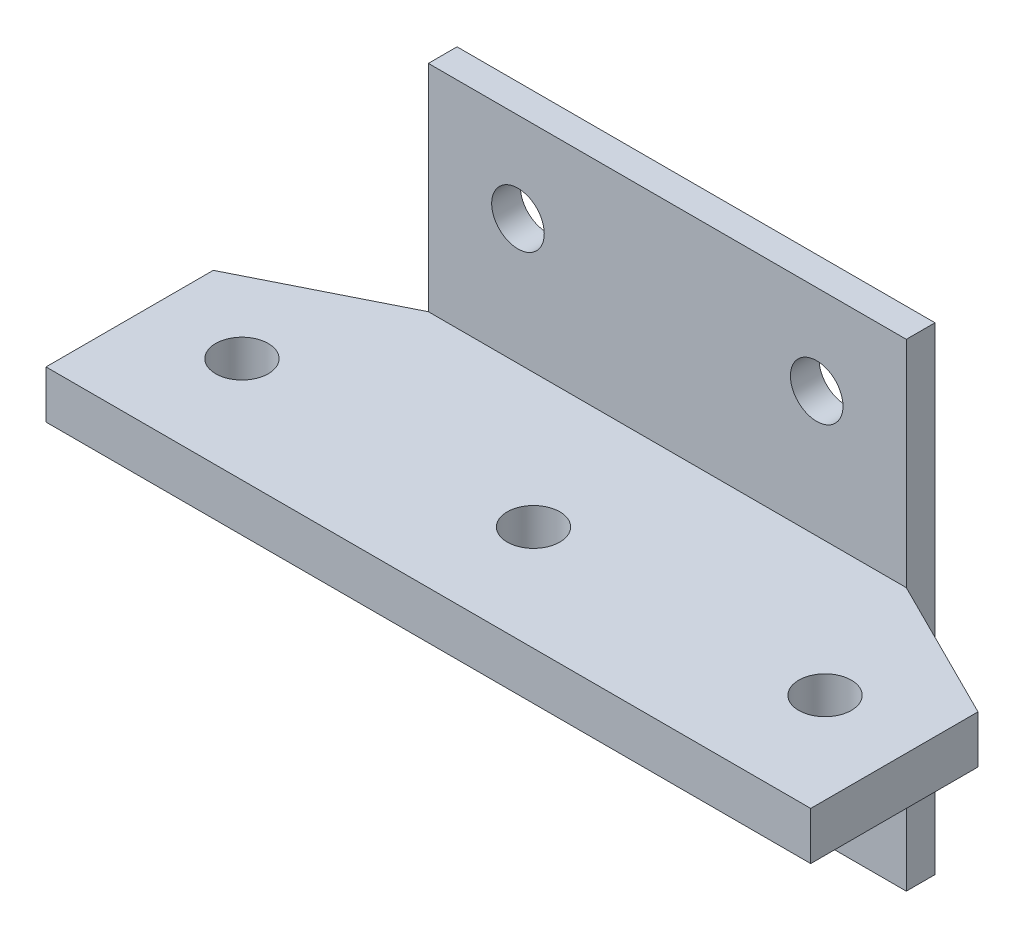
SolidWorks part; units mm, degrees
ref_plane "前视基准面" through (0, 0, 0) normal (0, 0, 1) x (1, 0, 0)
ref_plane "上视基准面" through (0, 0, 0) normal (0, 1, 0) x (1, 0, 0)
ref_plane "右视基准面" through (0, 0, 0) normal (1, 0, 0) x (0, 0, -1)
sketch "草图1" plane through (0, 0, 0) normal (0, 0, 1) x (1, 0, 0)
  line L1 (0, 0) -> (200, 0)
  line L2 (0, 0) -> (0, 200)
  line L3 (0, 200) -> (200, 200)
  line L4 (200, 0) -> (200, 200)
  dimension "D1" = 200
  dimension "D2" = 200
extrude "拉伸1" add sketch "草图1" along normal blind 12
sketch "草图2" plane through (0, 0, 12) normal (0, 0, 1) x (1, 0, 0)
  line L0 (0, 200) -> (0, 0) construction
  line L1 (0, 0) -> (200, 0) construction
  circle A0 centre (37.5, 37.5) radius 11
  dimension "D1" = 37.5
  dimension "D3" = 22
  dimension "D2" = 37.5
extrude "拉伸2" cut sketch "草图2" against normal through all
pattern_linear "阵列(线性)1" count 2 spacing 125 along (1, 0, 0) count 2 spacing 125 along (0, 1, 0) of "拉伸2"
sketch "草图3" plane through (0, 0, 12) normal (0, 0, 1) x (1, 0, 0)
  line L0 (0, 0) -> (200, 0) construction
  line L1 (-60, 110) -> (260, 110)
  line L2 (-60, 110) -> (-60, 90)
  line L3 (-60, 90) -> (260, 90)
  line L4 (260, 110) -> (260, 90)
  line L7 (0, 200) -> (0, 0) construction
  line L10 (200, 0) -> (200, 200) construction
  dimension "D1" = 20
  dimension "D2" = 60
  dimension "D3" = 60
  dimension "D4" = 90
extrude "拉伸3" add sketch "草图3" along normal blind 100
sketch "草图4" plane through (0, 90, 0) normal (0, -1, 0) x (1, 0, 0)
  line L0 (200, 12) -> (260, 42)
  line L1 (200, 12) -> (260, 12) construction
  line L2 (260, 112) -> (260, 12) construction
  line L3 (-60, 42) -> (0, 12)
  line L4 (-60, 112) -> (-60, 12) construction
  line L5 (260, 42) -> (260, 12)
  line L6 (260, 12) -> (200, 12)
  line L7 (-60, 42) -> (-60, 12)
  line L8 (-60, 12) -> (0, 12)
  dimension "D1" = 30
  dimension "D2" = 30
extrude "拉伸4" cut sketch "草图4" against normal through all
sketch "草图6" plane through (0, 90, 0) normal (0, -1, 0) x (1, 0, 0)
  line L0 (-60, 112) -> (-60, 42) construction
  line L1 (-60, 112) -> (260, 112) construction
  circle A0 centre (-22, 68) radius 11
  dimension "D1" = 38
  dimension "D3" = 22
  dimension "D2" = 44
extrude "拉伸6" cut sketch "草图6" against normal through all
pattern_linear "阵列(线性)3" count 3 spacing 122 along (1, 0, 0) of "拉伸6"
